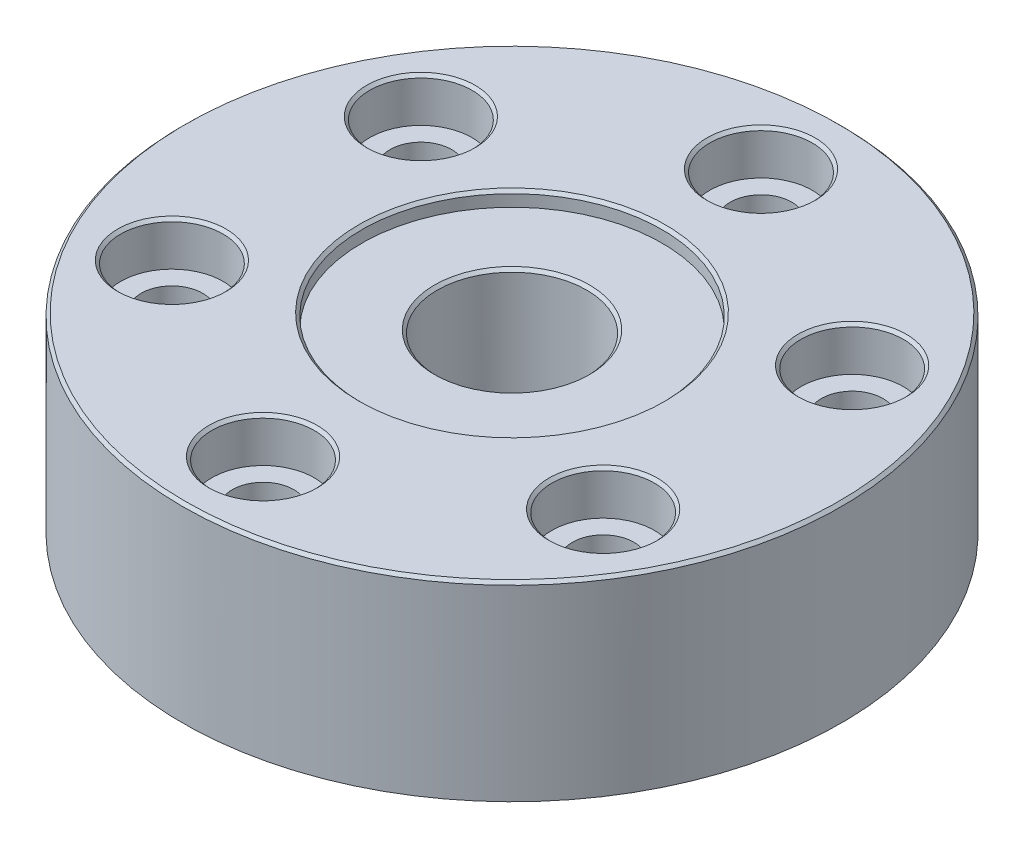
SolidWorks part; units mm, degrees
ref_plane "Front Plane" through (0, 0, 0) normal (0, 0, 1) x (1, 0, 0)
ref_plane "Top Plane" through (0, 0, 0) normal (0, 1, 0) x (1, 0, 0)
ref_plane "Right Plane" through (0, 0, 0) normal (1, 0, 0) x (0, 0, -1)
other "Configuration Table"
sketch "草图1" plane through (0, 0, 0) normal (0, 0, 1) x (1, 0, 0)
  line L0 (22.5, 13) -> (0, 13)
  line L1 (0, 13) -> (0, 0)
  line L2 (0, 0) -> (22.5, 0)
  line L3 (22.5, 0) -> (22.5, 13)
  line L4 (0, 13) -> (0, 0) construction
revolve "旋转1" add sketch "草图1" angle 360 about L4
hole_wizard "M3.5 六角头机械螺钉的柱形沉头孔1" positions "草图3" profile "草图2" counterbore size "M3.5" standard "ANSI Metric" end condition through all
sketch "草图3" plane through (0, 13, 0) normal (0, 1, 0) x (1, 0, 0)
  point P0 (14.7224, 8.5)
  point P1 (14.7224, -8.5)
  point P2 (0, -17)
  point P3 (-14.7224, -8.5)
  point P4 (-14.7224, 8.5)
  point P5 (0, 17)
sketch "草图2" plane through (14.7224, 13, -8.5) normal (1, 0, 0) x (0, 0, 1)
  line L0 (0, 0) -> (0, 13)
  line L1 (0, 13) -> (2.1, 13)
  line L3 (2.1, 13) -> (2.1, 3)
  line L4 (2.1, 3) -> (3.5, 3)
  line L5 (3.5, 3) -> (3.5, 0)
  line L7 (3.5, 0) -> (0, 0)
  line L11 (0, -6.35) -> (0, 107.95) construction
  dimension "通孔孔直径" = 4.2
  dimension "通孔孔深度" = 13
  dimension "柱形沉头孔直径" = 7
  dimension "柱形沉头孔深度" = 3
hole_wizard "孔1" positions "草图5" profile "草图4" legacy
sketch "草图5" plane through (0, 13, 0) normal (0, 1, 0) x (1, 0, 0)
  point P0 (0, 0)
sketch "草图4" plane through (0, 13, 0) normal (1, 0, 0) x (0, 0, 1)
  line L0 (0, 0) -> (0, 13)
  line L1 (0, 13) -> (5.1, 13)
  line L2 (5.1, 13) -> (5.1, 1)
  line L3 (5.1, 1) -> (10.25, 1)
  line L4 (10.25, 1) -> (10.25, 0)
  line L5 (10.25, 0) -> (0, 0)
  line L6 (0, 110) -> (0, -10) construction
  dimension "直径" = 10.2
  dimension "深度" = 13
  dimension "柱坑直径" = 20.5
  dimension "柱坑深度" = 1
chamfer "倒角1" distance 0.2 angle 45 9 edges at (0, 12, 5.1) (0, 13, 10.25) (14.7224, 13, 12) (0, 13, 20.5) (-14.7224, 13, 12) (14.7224, 13, -5) (0, 13, -13.5) (-14.7224, 13, -5) (0, 13, -22.5)
